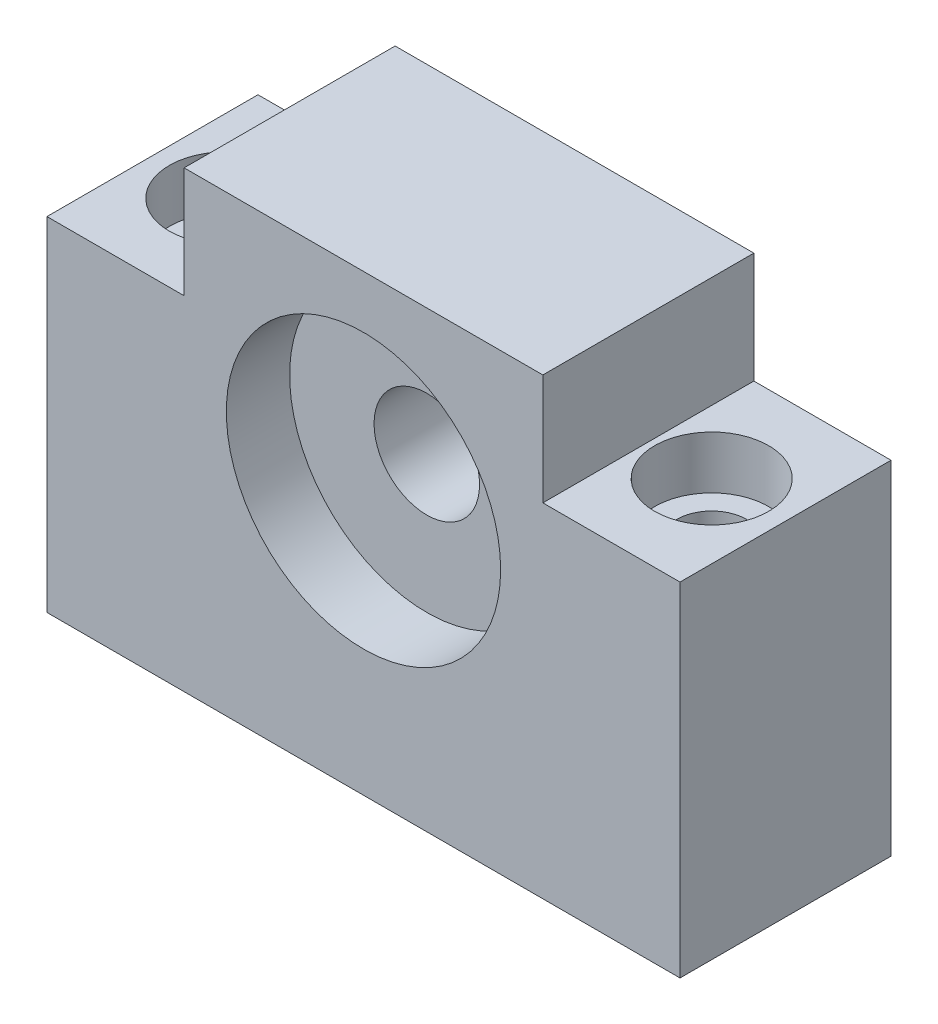
SolidWorks part; units mm, degrees
ref_plane "Plan de face" through (0, 0, 0) normal (0, 0, 1) x (1, 0, 0)
ref_plane "Plan de dessus" through (0, 0, 0) normal (0, 1, 0) x (1, 0, 0)
ref_plane "Plan de droite" through (0, 0, 0) normal (1, 0, 0) x (0, 0, -1)
sketch "Esquisse1" plane through (0, 0, 0) normal (0, 0, 1) x (1, 0, 0)
  line L0 (-27.862, -13.9359) -> (32.138, -13.9359)
  line L1 (32.138, -13.9359) -> (32.138, 18.5641)
  line L2 (32.138, 18.5641) -> (19.138, 18.5641)
  line L3 (19.138, 18.5641) -> (19.138, 29.0641)
  line L4 (19.138, 29.0641) -> (-14.862, 29.0641)
  line L5 (-14.862, 29.0641) -> (-14.862, 18.5641)
  line L6 (-14.862, 18.5641) -> (-27.862, 18.5641)
  line L7 (-27.862, 18.5641) -> (-27.862, -13.9359)
  circle A0 centre (2.138, 11.0641) radius 5
  point P2 (2.138, -13.9359)
  point P9 (2.138, 29.0641)
  dimension "D5" = 10
  dimension "D1" = 60
  dimension "D2" = 34
  dimension "D3" = 32.5
  dimension "D4" = 43
  dimension "D6" = 25
extrude "Boss.-Extru.1" add sketch "Esquisse1" along normal blind 20
sketch "Esquisse2" plane through (0, 18.5641, 0) normal (0, 1, 0) x (1, 0, 0)
  line L0 (32.138, -20) -> (32.138, 0) construction
  circle A1 centre (25.138, -10) radius 3.3
  circle A3 centre (-20.862, -10) radius 3.3
  point P13 (32.138, -10)
  dimension "D4" = 6.6
  dimension "D1" = 46
extrude "Enlèv. mat.-Extru.1" cut sketch "Esquisse2" against normal up to next
sketch "Esquisse3" plane through (0, 18.5641, 0) normal (0, 1, 0) x (1, 0, 0)
  circle A1 centre (25.138, -10) radius 5.4
  circle A2 centre (-20.862, -10) radius 5.4
  dimension "D1" = 10.8
extrude "Enlèv. mat.-Extru.2" cut sketch "Esquisse3" against normal blind 5
sketch "Esquisse4" plane through (0, 0, 20) normal (0, 0, 1) x (1, 0, 0)
  circle A0 centre (2.138, 11.0641) radius 13
  dimension "D1" = 26
extrude "Enlèv. mat.-Extru.3" cut sketch "Esquisse4" against normal blind 6
sketch "Esquisse5" plane through (0, 0, 0) normal (0, 0, -1) x (-1, 0, 0)
  circle A0 centre (-2.138, 11.0641) radius 13
  dimension "D1" = 26
extrude "Enlèv. mat.-Extru.4" cut sketch "Esquisse5" against normal blind 6
